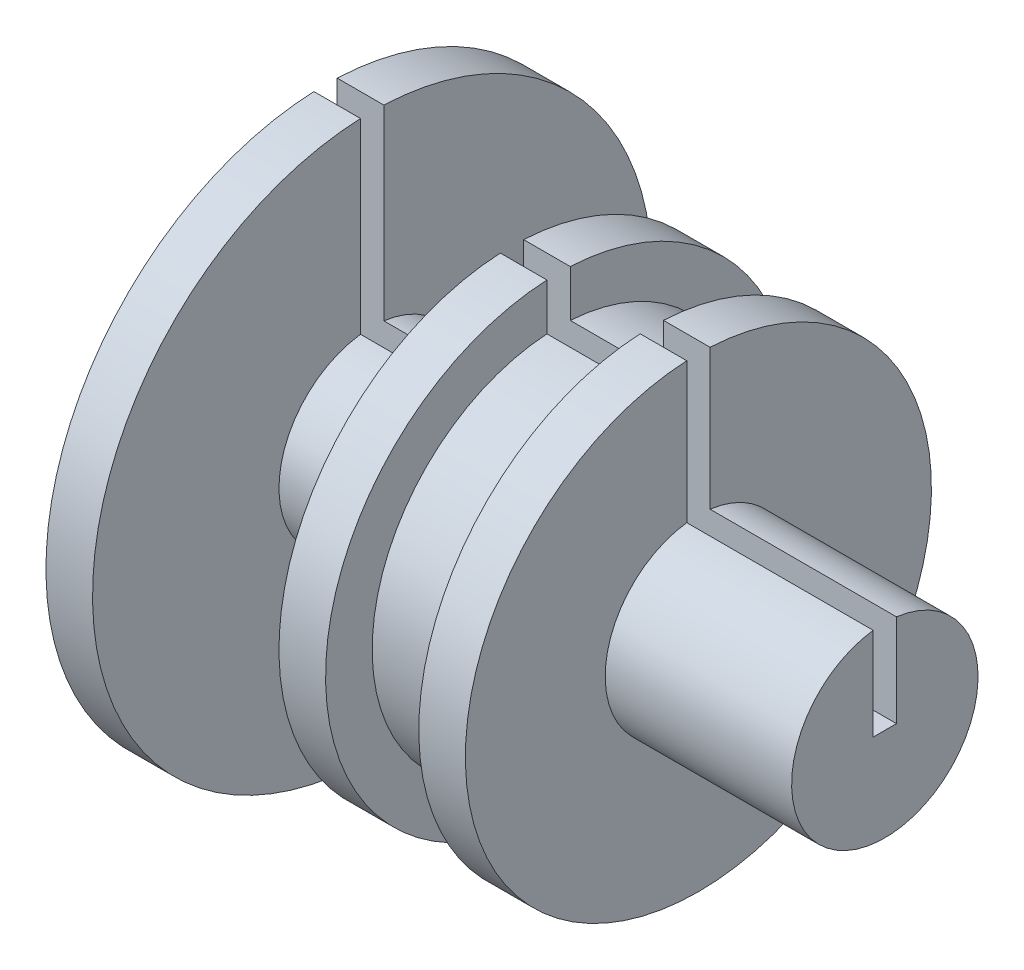
SolidWorks part; units mm, degrees
ref_plane "Front Plane" through (0, 0, 0) normal (0, 0, 1) x (1, 0, 0)
ref_plane "Top Plane" through (0, 0, 0) normal (0, 1, 0) x (1, 0, 0)
ref_plane "Right Plane" through (0, 0, 0) normal (1, 0, 0) x (0, 0, -1)
sketch "Sketch1" plane through (0, 0, 0) normal (0, 0, 1) x (1, 0, 0)
  line L0 (0, 0) -> (60, 0) construction
  line L2 (20, 10) -> (5, 10)
  line L3 (20, 10) -> (20, 25)
  line L4 (20, 25) -> (25, 25)
  line L5 (25, 25) -> (25, 20)
  line L6 (25, 20) -> (35, 20)
  line L7 (35, 25) -> (35, 20)
  line L8 (40, 25) -> (35, 25)
  line L9 (40, 10) -> (40, 25)
  line L10 (60, 10) -> (40, 10)
  line L11 (60, 0) -> (60, 10)
  line L12 (30, 0) -> (30, 40) construction
  line L13 (0, 0) -> (60, 0)
  line L14 (5, 10) -> (5, 30)
  line L15 (5, 30) -> (0, 30)
  line L16 (0, 30) -> (0, 0)
  point P13 (30, 20)
  dimension "D1" = 5
  dimension "D2" = 10
  dimension "D3" = 50
  dimension "D4" = 5
  dimension "D5" = 30
  dimension "D6" = 20
  dimension "D7" = 5
revolve "Revolve1" add sketch "Sketch1" angle 360 about L13
sketch "Sketch2" plane through (60, 0, 0) normal (1, 0, 0) x (0, 0, -1)
  line L1 (-1.25, 34.957) -> (1.25, 34.957)
  line L2 (-1.25, 34.957) -> (-1.25, 0)
  line L3 (-1.25, 0) -> (1.25, 0)
  line L4 (1.25, 34.957) -> (1.25, 0)
  point P4 (0, 0)
  dimension "D1" = 34.957
  dimension "D2" = 2.5
extrude "Cut-Extrude1" cut sketch "Sketch2" against normal through all
